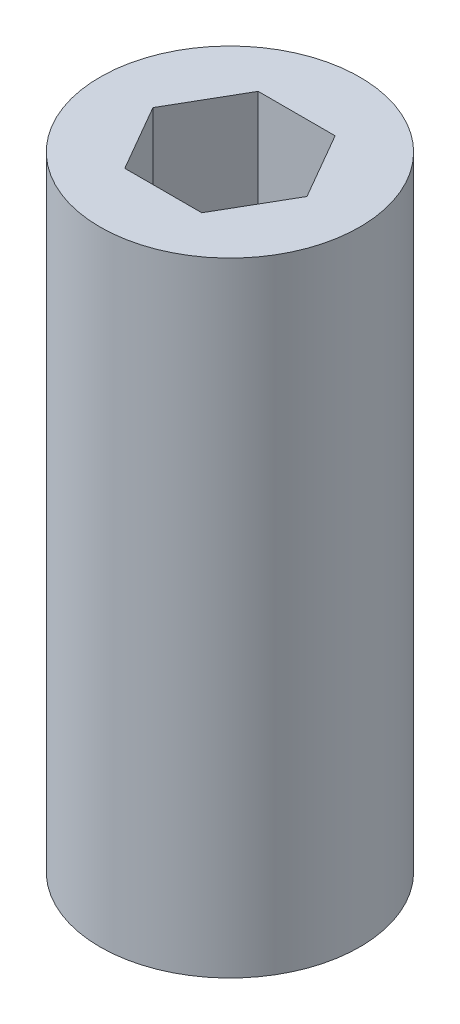
SolidWorks part; units mm, degrees
material "PET"
ref_plane "Front Plane" through (0, 0, 0) normal (0, 0, 1) x (1, 0, 0)
ref_plane "Top Plane" through (0, 0, 0) normal (0, 1, 0) x (1, 0, 0)
ref_plane "Right Plane" through (0, 0, 0) normal (1, 0, 0) x (0, 0, -1)
sketch "Sketch1" plane through (0, 0, 0) normal (0, 1, 0) x (1, 0, 0)
  line L1 (5.6459, 0) -> (2.823, 4.8895)
  line L2 (2.823, 4.8895) -> (-2.823, 4.8895)
  line L3 (-2.823, 4.8895) -> (-5.6459, 0)
  line L4 (-5.6459, 0) -> (-2.823, -4.8895)
  line L5 (-2.823, -4.8895) -> (2.823, -4.8895)
  line L6 (2.823, -4.8895) -> (5.6459, 0)
  circle A0 centre (0, 0) radius 4.8895 construction
  circle A1 centre (0, 0) radius 9.525
  dimension "D1" = 9.779
  dimension "D2" = 19.05
extrude "Boss-Extrude1" add sketch "Sketch1" along normal blind 45.72
